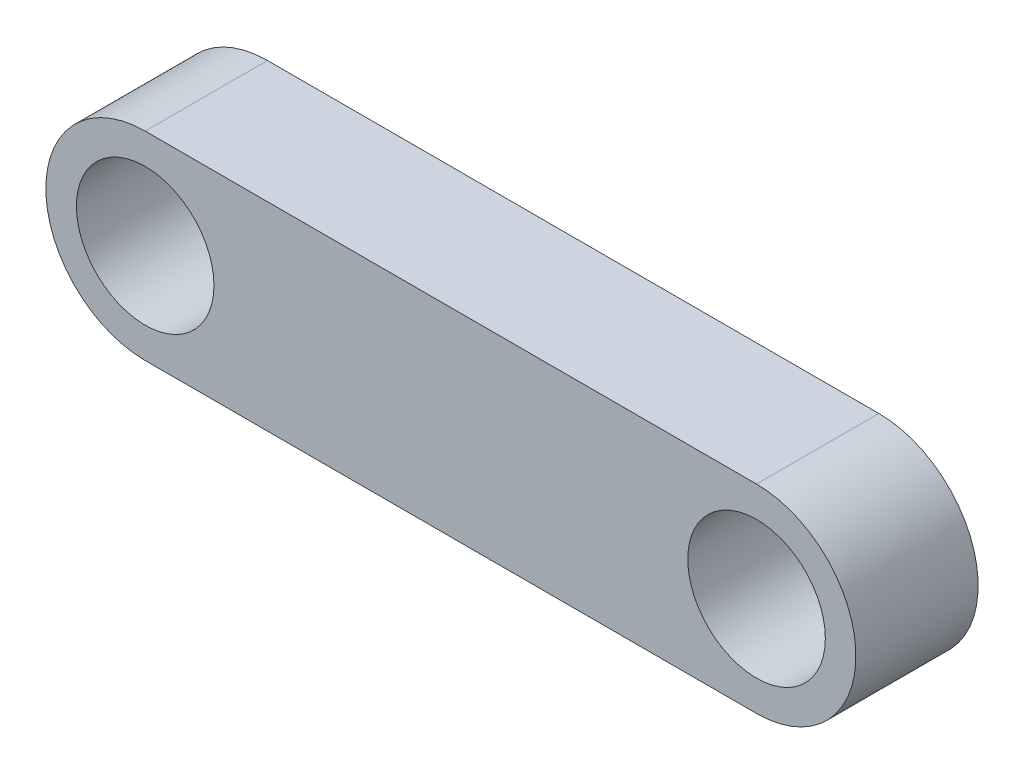
SolidWorks part; units mm, degrees
ref_plane "Front Plane" through (0, 0, 0) normal (0, 0, 1) x (1, 0, 0)
ref_plane "Top Plane" through (0, 0, 0) normal (0, 1, 0) x (1, 0, 0)
ref_plane "Right Plane" through (0, 0, 0) normal (1, 0, 0) x (0, 0, -1)
sketch "Sketch1" plane through (0, 0, 0) normal (0, 0, 1) x (1, 0, 0)
  line L0 (0, 3.25) -> (20, 3.25)
  line L1 (0, -3.25) -> (20, -3.25)
  arc A0 (0, 3.25) -> (0, -3.25) centre (0, 0) ccw
  circle A1 centre (0, 0) radius 2.25
  arc A2 (20, -3.25) -> (20, 3.25) centre (20, 0) ccw
  circle A3 centre (20, 0) radius 2.25
  dimension "D1" = 6.5
  dimension "D2" = 4.5
  dimension "D4" = 20
  dimension "D3" = 2
extrude "Boss-Extrude1" add sketch "Sketch1" along normal mid plane 4
